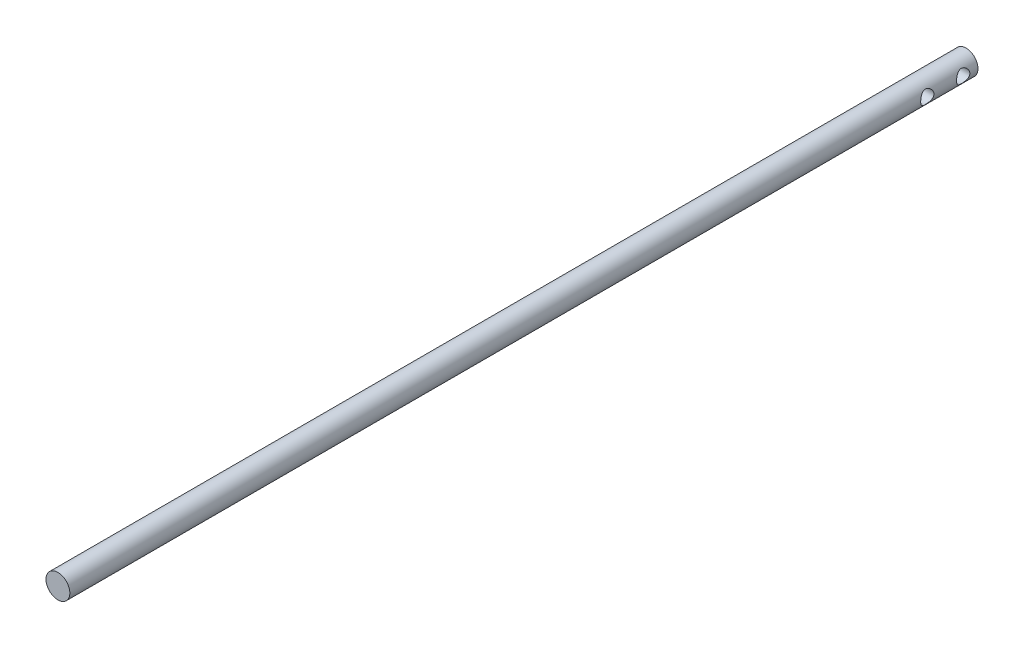
SolidWorks part; units mm, degrees
ref_plane "Front Plane" through (0, 0, 0) normal (0, 0, 1) x (1, 0, 0)
ref_plane "Top Plane" through (0, 0, 0) normal (0, 1, 0) x (1, 0, 0)
ref_plane "Right Plane" through (0, 0, 0) normal (1, 0, 0) x (0, 0, -1)
sketch "Sketch1" plane through (0, 0, 0) normal (0, 0, 1) x (1, 0, 0)
  line L0 (0, 7.0089) -> (0, -7.1621) construction
  circle A0 centre (0, 0) radius 3.81
  dimension "D1" = 7.62
extrude "Boss-Extrude1" add sketch "Sketch1" along normal blind 290.195
ref_plane "Plane7" through (5.08, 0, 0) normal (1, 0, 0) x (0, 0, -1)
sketch "Sketch8" plane through (5.08, 0, 0) normal (1, 0, 0) x (0, 0, -1)
  circle A0 centre (-4.7256, 0) radius 2.1176
  circle A1 centre (-16.1884, 0) radius 2.1176
  point P4 (0, 0)
extrude "Cut-Extrude4" cut sketch "Sketch8" against normal blind 28.702
